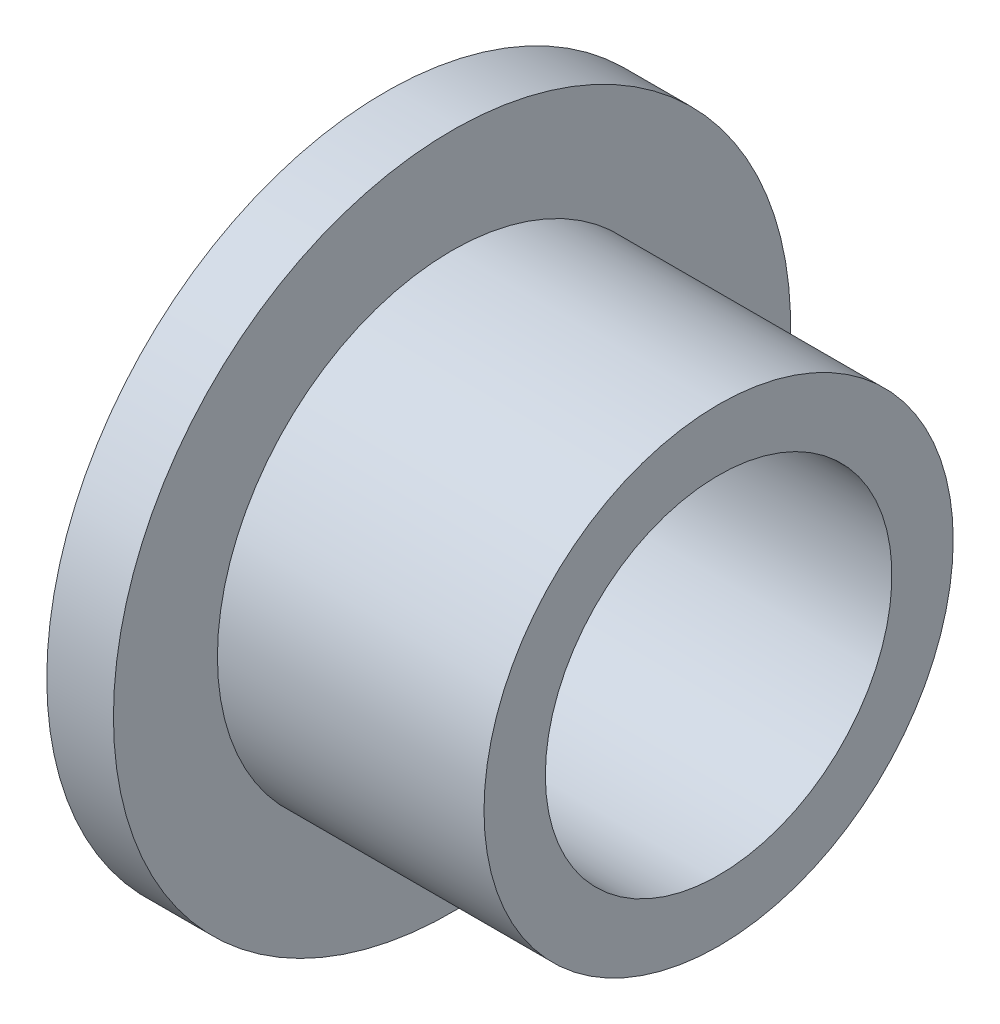
SolidWorks part; units mm, degrees
ref_plane "Front Plane" through (0, 0, 0) normal (0, 0, 1) x (1, 0, 0)
ref_plane "Top Plane" through (0, 0, 0) normal (0, 1, 0) x (1, 0, 0)
ref_plane "Right Plane" through (0, 0, 0) normal (1, 0, 0) x (0, 0, -1)
ref_plane "Plane1" through (0, 0, 0) normal (0, 0, -1) x (-1, 0, 0)
sketch "Sketch1" plane through (0, 0, 0) normal (0, 0, -1) x (-1, 0, 0)
  line L0 (0, 5.588) -> (0, 4.1275)
  line L1 (0, 4.1275) -> (7.9375, 4.1275)
  line L2 (7.9375, 4.1275) -> (7.9375, 8.0645)
  line L3 (7.9375, 8.0645) -> (6.35, 8.0645)
  line L4 (6.35, 8.0645) -> (6.35, 5.588)
  line L5 (6.35, 5.588) -> (0, 5.588)
  line L6 (0, 0) -> (7.9375, 0) construction
revolve "Revolve1" add sketch "Sketch1" angle 360 about L6
scale "Scale1" scale about centroid uniform scaling yes scale factor 0.484262
